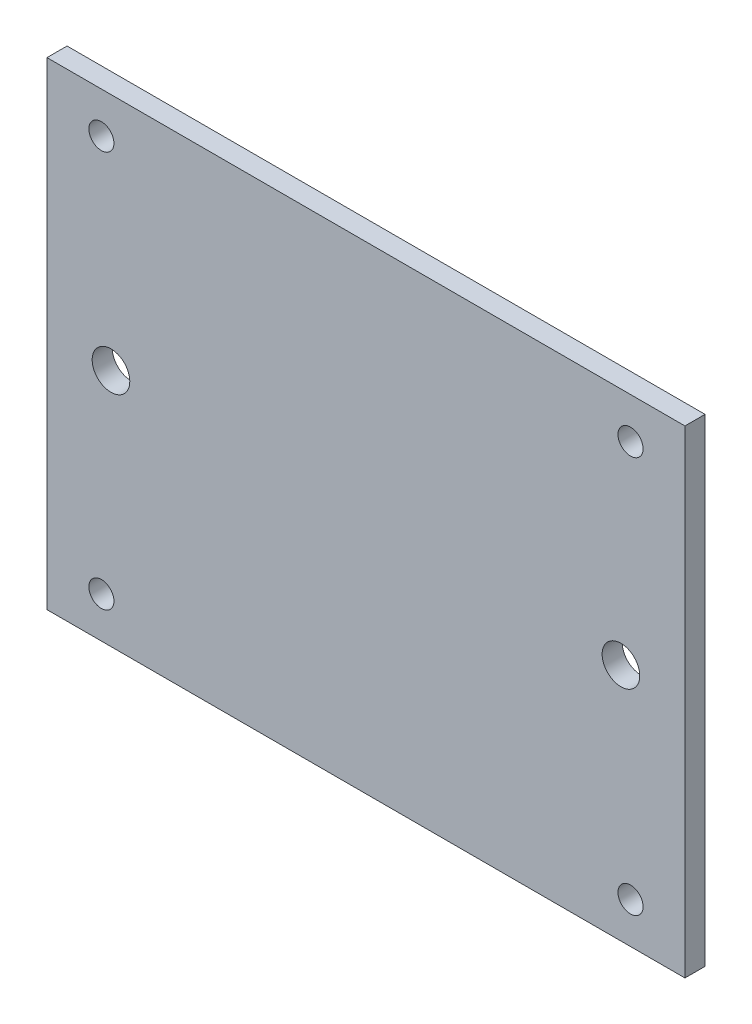
SolidWorks part; units mm, degrees
ref_plane "Front Plane" through (0, 0, 0) normal (0, 0, 1) x (1, 0, 0)
ref_plane "Top Plane" through (0, 0, 0) normal (0, 1, 0) x (1, 0, 0)
ref_plane "Right Plane" through (0, 0, 0) normal (1, 0, 0) x (0, 0, -1)
sketch "Sketch1" plane through (0, 0, 0) normal (0, 0, 1) x (1, 0, 0)
  line L0 (0, -40.427) -> (0, 40.427) construction
  line L1 (-25.42, -19.05) -> (25.42, -19.05)
  line L2 (-25.42, -19.05) -> (-25.42, 19.05)
  line L3 (-25.42, 19.05) -> (25.42, 19.05)
  line L4 (25.42, -19.05) -> (25.42, 19.05)
  line L5 (-25.42, -19.05) -> (25.42, 19.05) construction
  line L6 (-25.42, 19.05) -> (25.42, -19.05) construction
  line L7 (-52.9839, 0) -> (52.9839, 0) construction
  circle A2 centre (-21.0833, 15.8) radius 1
  circle A3 centre (21.0833, 15.8) radius 1
  circle A4 centre (21.0833, -15.8) radius 1
  circle A5 centre (-21.0833, -15.8) radius 1
  circle A6 centre (-20.32, 0) radius 1.5
  circle A7 centre (20.32, 0) radius 1.5
  point P0 (0, 0)
  point P9 (0, 0)
  point P11 (-21.82, 0)
  point P14 (0, 0)
  point P15 (21.82, 0)
  dimension "D5" = 2
  dimension "D7" = 3
  dimension "D8" = 5.1
  dimension "D1" = 50.84
  dimension "D2" = 38.1
  dimension "D6" = 3.25
extrude "Boss-Extrude1" add sketch "Sketch1" along normal blind 1.6
